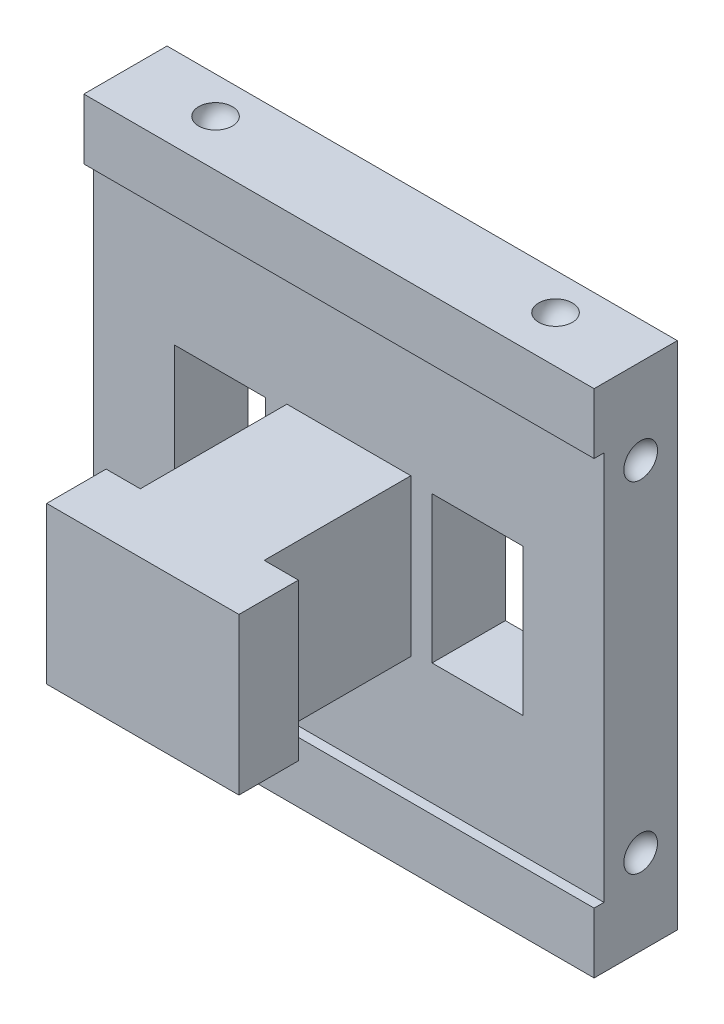
SolidWorks part; units mm, degrees
ref_plane "正面" through (0, 0, 0) normal (0, 0, 1) x (1, 0, 0)
ref_plane "平面" through (0, 0, 0) normal (0, 1, 0) x (1, 0, 0)
ref_plane "右側面" through (0, 0, 0) normal (1, 0, 0) x (0, 0, -1)
sketch "ｽｹｯﾁ1" plane through (0, 0, 0) normal (0, 0, 1) x (1, 0, 0)
  line L0 (6.375, 23.65) -> (6.375, 0) construction
  line L1 (0, 0) -> (12.75, 0)
  line L2 (0, 0) -> (0, 23.65)
  line L3 (0, 23.65) -> (12.75, 23.65)
  line L4 (12.75, 0) -> (12.75, 23.65) construction
  line L5 (19.375, 23.65) -> (19.375, 0) construction
  line L6 (12.75, 23.65) -> (25.755, 23.65)
  line L7 (12.75, 0) -> (25.755, 0)
  line L8 (25.755, 0) -> (25.755, 23.65)
  line L9 (12.75, 11.825) -> (0, 11.825) construction
  dimension "D2" = 12.75
  dimension "D3" = 13
  dimension "D4" = 6.38
extrude "ﾎﾞｽ - 押し出し1" add sketch "ｽｹｯﾁ1" along normal blind 3.7
sketch "ｽｹｯﾁ2" plane through (0, 0, 3.7) normal (0, 0, 1) x (1, 0, 0)
  line L0 (12.8775, 23.65) -> (12.8775, 0) construction
  line L1 (19.375, 15.525) -> (19.375, 23.65) construction
  line L2 (8.68, 15.525) -> (8.68, 8.125)
  line L3 (17.075, 15.525) -> (17.075, 8.125)
  line L4 (4.08, 15.525) -> (8.68, 15.525)
  line L5 (4.08, 15.525) -> (4.08, 8.125)
  line L6 (4.08, 8.125) -> (8.68, 8.125)
  line L9 (6.38, 23.65) -> (6.38, 0) construction
  line L10 (25.755, 23.65) -> (0, 23.65) construction
  line L11 (0, 0) -> (25.755, 0) construction
  line L12 (0, 23.65) -> (0, 0) construction
  line L13 (21.675, 8.125) -> (17.075, 8.125)
  line L14 (21.675, 15.525) -> (21.675, 8.125)
  line L15 (21.675, 15.525) -> (17.075, 15.525)
  dimension "D5" = 6.38
extrude "ｶｯﾄ - 押し出し1" cut sketch "ｽｹｯﾁ2" against normal up to next
sketch "ｽｹｯﾁ3" plane through (0, 0, 3.7) normal (0, 0, 1) x (1, 0, 0)
  line L1 (25.755, 0) -> (25.755, 23.65) construction
  line L2 (0, 23.65) -> (25.755, 23.65)
  line L3 (0, 23.65) -> (0, 21.65)
  line L4 (0, 21.65) -> (25.755, 21.65)
  line L5 (25.755, 23.65) -> (25.755, 21.65)
  line L7 (0, 0) -> (25.755, 0)
  line L8 (0, 0) -> (0, 2)
  line L9 (0, 2) -> (25.755, 2)
  line L10 (25.755, 0) -> (25.755, 2)
  dimension "D1" = 2
  dimension "D2" = 2
extrude "ﾎﾞｽ - 押し出し2" add sketch "ｽｹｯﾁ3" along normal blind 1
sketch "ｽｹｯﾁ4" plane through (0, 0, 3.7) normal (0, 0, 1) x (1, 0, 0)
  line L0 (8.68, 8.125) -> (8.68, 15.525) construction
  line L1 (0, 21.65) -> (0, 2) construction
  line L2 (9.75, 7.875) -> (16.005, 7.875)
  line L3 (12.8775, 15.525) -> (12.8775, 21.65) construction
  line L4 (0, 15.775) -> (2.95, 15.775)
  line L5 (0, 15.775) -> (0, 7.875)
  line L6 (0, 7.875) -> (2.95, 7.875)
  line L7 (2.95, 15.775) -> (2.95, 7.875)
  line L8 (9.75, 15.775) -> (9.75, 7.875)
  line L9 (0, 21.65) -> (25.755, 21.65) construction
  line L10 (16.005, 15.775) -> (16.005, 7.875)
  line L11 (9.75, 15.775) -> (16.005, 15.775)
  line L12 (17.075, 15.525) -> (17.075, 8.125) construction
  line L13 (0, 5.152) -> (25.755, 5.152) construction
  line L14 (25.755, 2) -> (25.755, 21.65) construction
  line L15 (12.8775, 5.152) -> (12.8775, 25.6744) construction
  line L16 (22.805, 15.775) -> (22.805, 7.875)
  line L17 (25.755, 7.875) -> (22.805, 7.875)
  line L18 (25.755, 15.775) -> (25.755, 7.875)
  line L19 (25.755, 15.775) -> (22.805, 15.775)
  dimension "D1" = 1.07
  dimension "D2" = 1.07
  dimension "D3" = 2.95
extrude "ﾎﾞｽ - 押し出し3" add sketch "ｽｹｯﾁ4" along normal blind 10.4
sketch "ｽｹｯﾁ5" plane through (0, 0, 14.1) normal (0, 0, 1) x (1, 0, 0)
  line L0 (12.8775, 21.65) -> (12.8775, 26.6538) construction
  line L6 (3, 11.825) -> (9.75, 11.825) construction
  line L7 (9.75, 15.775) -> (9.75, 7.875) construction
  line L8 (6.375, 11.825) -> (6.375, 21.65) construction
  line L9 (16.005, 15.775) -> (17.73, 15.775)
  line L10 (0, 21.65) -> (25.755, 21.65) construction
  line L11 (8.025, 15.775) -> (8.025, 7.875)
  line L12 (9.75, 7.875) -> (8.025, 7.875)
  line L13 (9.75, 15.775) -> (9.75, 7.875)
  line L14 (9.75, 15.775) -> (8.025, 15.775)
  line L15 (16.005, 15.775) -> (16.005, 7.875)
  line L16 (16.005, 7.875) -> (17.73, 7.875)
  line L17 (17.73, 15.775) -> (17.73, 7.875)
extrude "ﾎﾞｽ - 押し出し4" add sketch "ｽｹｯﾁ5" against normal blind 3
sketch "ｽｹｯﾁ9" plane through (0, 7.875, 0) normal (0, -1, 0) x (1, 0, 0)
  line L0 (0, 4.7) -> (2.95, 4.7)
  line L1 (0, 4.7) -> (25.755, 4.7) construction
  line L2 (22.805, 4.7) -> (25.755, 4.7)
  line L4 (0, 3.7) -> (2.95, 3.7)
  line L5 (2.95, 3.7) -> (2.95, 14.1)
  line L6 (2.95, 14.1) -> (0, 14.1)
  line L7 (0, 14.1) -> (0, 3.7)
  line L9 (2.95, 4.7) -> (2.95, 14.1)
  line L10 (2.95, 14.1) -> (0, 14.1)
  line L11 (0, 14.1) -> (0, 4.7)
  line L12 (22.805, 3.7) -> (25.755, 3.7)
  line L13 (25.755, 3.7) -> (25.755, 14.1)
  line L14 (25.755, 14.1) -> (22.805, 14.1)
  line L15 (22.805, 14.1) -> (22.805, 3.7)
  line L17 (25.755, 4.7) -> (25.755, 14.1)
  line L18 (25.755, 14.1) -> (22.805, 14.1)
  line L19 (22.805, 14.1) -> (22.805, 4.7)
  dimension "D1" = 0
  dimension "D2" = 0
extrude "ｶｯﾄ - 押し出し4" cut sketch "ｽｹｯﾁ9" against normal up to vertex
fillet "ﾌｨﾚｯﾄ2" radius 0.4 2 edges at (22.805, 11.825, 4.7) (2.95, 11.825, 4.7)
sketch "ｽｹｯﾁ10" plane through (0, 0, 0) normal (-1, 0, 0) x (0, 0, 1)
  line L0 (4.7, 23.65) -> (0, 23.65) construction
  line L1 (4.7, 23.65) -> (2.079, 23.65)
  line L2 (4.7, 23.65) -> (4.7, 25.15)
  line L3 (4.7, 25.15) -> (2.079, 25.15)
  line L4 (2.079, 23.65) -> (2.079, 25.15)
  line L5 (4.7, 23.65) -> (4.7, 21.65) construction
  line L6 (0, 11.825) -> (-6.9736, 11.825) construction
  line L7 (4.7, -1.5) -> (2.079, -1.5)
  line L8 (4.7, 0) -> (4.7, -1.5)
  line L9 (4.7, 0) -> (2.079, 0)
  line L10 (2.079, 0) -> (2.079, -1.5)
  dimension "D1" = 1.5
extrude "ﾎﾞｽ - 押し出し5" [suppressed] add sketch "ｽｹｯﾁ10" against normal up to vertex
sketch "ｽｹｯﾁ11" plane through (0, 7.875, 0) normal (0, -1, 0) x (1, 0, 0)
  line L0 (2.95, 3.7) -> (2.95, 4.3) construction
  line L1 (2.55, 4.7) -> (0, 4.7) construction
  line L2 (0, 4.7) -> (0, 3.7) construction
  line L3 (0, 3.7) -> (2.95, 3.7) construction
  line L4 (25.755, 4.7) -> (23.205, 4.7) construction
  line L5 (22.805, 4.3) -> (22.805, 3.7) construction
  line L6 (22.805, 3.7) -> (25.755, 3.7) construction
  line L7 (25.755, 3.7) -> (25.755, 4.7) construction
  line L8 (2.95, 3.7) -> (2.95, 4.3)
  line L9 (2.55, 4.7) -> (0, 4.7)
  line L10 (0, 4.7) -> (0, 3.7)
  line L11 (0, 3.7) -> (2.95, 3.7)
  line L12 (25.755, 4.7) -> (23.205, 4.7)
  line L13 (22.805, 4.3) -> (22.805, 3.7)
  line L14 (22.805, 3.7) -> (25.755, 3.7)
  line L15 (25.755, 3.7) -> (25.755, 4.7)
  arc A0 (2.95, 4.3) -> (2.55, 4.7) centre (2.55, 4.3) ccw construction
  arc A1 (23.205, 4.7) -> (22.805, 4.3) centre (23.205, 4.3) ccw construction
  arc A2 (2.95, 4.3) -> (2.55, 4.7) centre (2.55, 4.3) ccw
  arc A3 (23.205, 4.7) -> (22.805, 4.3) centre (23.205, 4.3) ccw
extrude "ｶｯﾄ - 押し出し5" cut sketch "ｽｹｯﾁ11" against normal up to vertex
sketch "ｽｹｯﾁ12" plane through (0, 0, 0) normal (-1, 0, 0) x (0, 0, 1)
  line L0 (3.7, 21.65) -> (3.7, 23.65)
  line L1 (3.7, 2) -> (3.7, 0)
  line L8 (4.7, 2) -> (3.7, 2)
  line L9 (3.7, 2) -> (3.7, 21.65)
  line L10 (3.7, 21.65) -> (4.7, 21.65)
  line L11 (4.7, 21.65) -> (4.7, 23.65)
  line L12 (4.7, 23.65) -> (0, 23.65)
  line L13 (0, 23.65) -> (0, 0)
  line L14 (0, 0) -> (4.7, 0)
  line L15 (4.7, 0) -> (4.7, 2)
  line L16 (4.7, 2) -> (3.7, 2)
  line L18 (3.7, 21.65) -> (4.7, 21.65)
  line L19 (4.7, 21.65) -> (4.7, 23.65)
  line L20 (4.7, 23.65) -> (3.7, 23.65)
  line L22 (3.7, 0) -> (4.7, 0)
  line L23 (4.7, 0) -> (4.7, 2)
  dimension "D1" = 0
extrude "ｶｯﾄ - 押し出し6" cut sketch "ｽｹｯﾁ12" against normal up to vertex
sketch "ｽｹｯﾁ13" plane through (0, 0, 0) normal (0, 0, -1) x (-1, 0, 0)
  line L0 (0, 24.705) -> (-25.755, 24.705)
  line L2 (-25.755, -1.055) -> (0, -1.055)
  line L4 (0, 0) -> (0, 23.65)
  line L5 (0, 23.65) -> (-25.755, 23.65)
  line L6 (-25.755, 23.65) -> (-25.755, 0)
  line L7 (-25.755, 0) -> (0, 0)
  line L9 (0, 23.65) -> (-25.755, 23.65)
  line L10 (-26.81, -1.055) -> (1.055, -1.055) construction
  line L11 (-25.755, 0) -> (0, 0)
  line L12 (-25.755, 23.65) -> (-25.755, 24.705)
  line L13 (0, 23.65) -> (0, 24.705)
  line L14 (0, 0) -> (0, -1.055)
  line L15 (-25.755, 0) -> (-25.755, -1.055)
  line L16 (-26.81, 24.705) -> (-26.81, -1.055) construction
  line L17 (1.055, 24.705) -> (-26.81, 24.705) construction
  line L18 (-25.755, 23.65) -> (-25.755, 0) construction
  line L19 (1.055, -1.055) -> (1.055, 24.705) construction
  line L20 (0, 0) -> (0, 23.65) construction
  dimension "D2" = 23.65
  dimension "D3" = 1.055
  dimension "D1" = 0
extrude "ﾎﾞｽ - 押し出し6" add sketch "ｽｹｯﾁ13" against normal up to vertex
sketch "ｽｹｯﾁ14" plane through (25.755, 0, 0) normal (1, 0, 0) x (0, 0, -1)
  line L0 (-1.85, 21.255) -> (-1.85, 19.555)
  line L1 (-3.7, 24.705) -> (0, 24.705) construction
  line L3 (-8.6565, 20.405) -> (-1.85, 20.405) construction
  line L4 (0, 11.825) -> (8.6335, 11.825) construction
  line L5 (0, -1.055) -> (0, 24.705) construction
  line L6 (-1.85, 2.395) -> (-1.85, 4.095)
  arc A0 (-1.85, 21.255) -> (-1.85, 19.555) centre (-1.85, 20.405) ccw
  arc A1 (-1.85, 2.395) -> (-1.85, 4.095) centre (-1.85, 3.245) cw
  dimension "D2" = 1.7
  dimension "D1" = 4.3
revolve "ｶｯﾄ - 回転1" cut sketch "ｽｹｯﾁ14" angle 180 about L0
ref_plane "平面1" through (12.8775, 0, 0) normal (1, 0, 0) x (0, 0, -1)
mirror "ﾐﾗｰ1" about plane through (12.8775, 0, 0) normal (1, 0, 0) of "ｶｯﾄ - 回転1"
sketch "ｽｹｯﾁ15" plane through (0, 24.705, 0) normal (0, 1, 0) x (1, 0, 0)
  line L0 (3.4475, -1.85) -> (5.1475, -1.85)
  line L1 (4.2975, -8.6565) -> (4.2975, -1.85) construction
  line L2 (12.8775, 0) -> (12.8775, 8.6335) construction
  line L3 (22.3075, -1.85) -> (20.6075, -1.85)
  arc A0 (3.4475, -1.85) -> (5.1475, -1.85) centre (4.2975, -1.85) ccw
  arc A1 (22.3075, -1.85) -> (20.6075, -1.85) centre (21.4575, -1.85) cw
revolve "ｶｯﾄ - 回転2" cut sketch "ｽｹｯﾁ15" angle 360 mid plane about L0
ref_plane "平面2" through (0, 11.825, 0) normal (0, -1, 0) x (-1, 0, 0)
mirror "ﾐﾗｰ2" about plane through (0, 11.825, 0) normal (0, -1, 0) of "ｶｯﾄ - 回転2"
sketch "ｽｹｯﾁ16" plane through (0, 0, 3.7) normal (0, 0, 1) x (1, 0, 0)
  line L0 (25.755, -1.055) -> (25.755, 24.705) construction
  line L1 (0, 24.705) -> (25.755, 24.705)
  line L2 (0, 24.705) -> (0, 21.65)
  line L3 (0, 21.65) -> (25.755, 21.65)
  line L4 (25.755, 24.705) -> (25.755, 21.65)
  line L5 (0, 11.825) -> (-17.7927, 11.825) construction
  line L6 (0, -1.055) -> (25.755, -1.055)
  line L7 (0, -1.055) -> (0, 2)
  line L8 (0, 2) -> (25.755, 2)
  line L9 (25.755, -1.055) -> (25.755, 2)
  line L10 (0, 24.705) -> (0, -1.055) construction
  line L11 (-2.035, 11.825) -> (2.035, 11.825) construction
  dimension "D1" = 9.825
  dimension "D2" = 9.825
extrude "ﾎﾞｽ - 押し出し7" add sketch "ｽｹｯﾁ16" along normal blind 0.5
